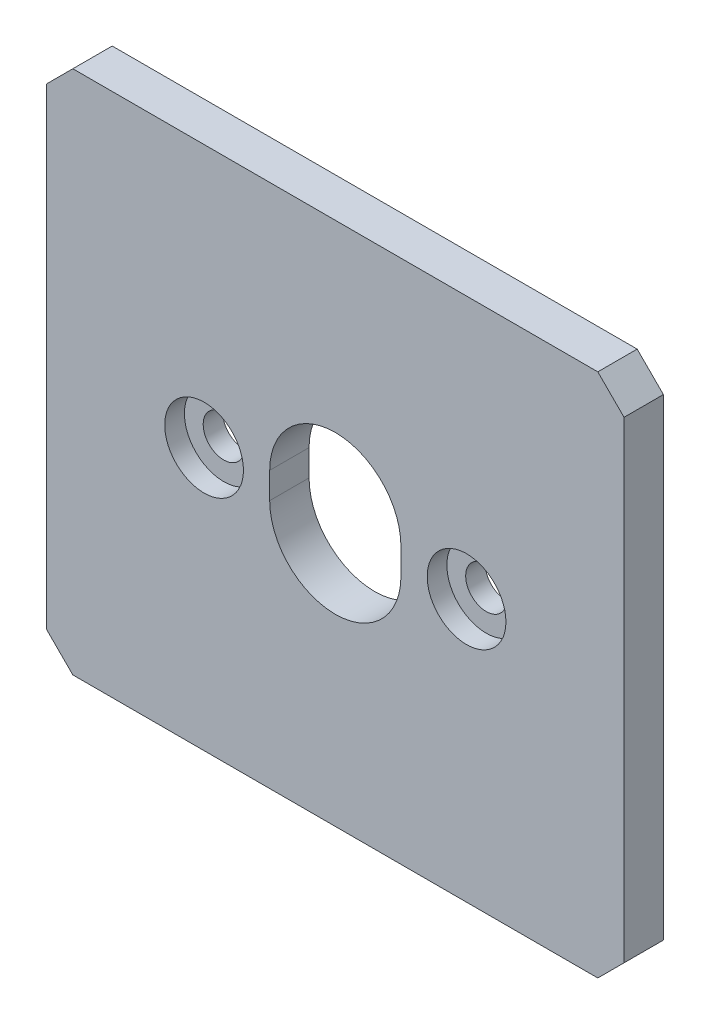
SolidWorks part; units mm, degrees
material "6063-T6"
ref_plane "Front Plane" through (0, 0, 0) normal (0, 0, 1) x (1, 0, 0)
ref_plane "Top Plane" through (0, 0, 0) normal (0, 1, 0) x (1, 0, 0)
ref_plane "Right Plane" through (0, 0, 0) normal (1, 0, 0) x (0, 0, -1)
sketch "Sketch1" plane through (0, 0, 0) normal (0, 0, 1) x (1, 0, 0)
  line L0 (0, 1.5875) -> (0, -1.5875) construction
  line L1 (-34.925, -31.75) -> (34.925, -31.75)
  line L2 (-34.925, -31.75) -> (-34.925, 31.75)
  line L3 (-34.925, 31.75) -> (34.925, 31.75)
  line L4 (34.925, -31.75) -> (34.925, 31.75)
  line L5 (-34.925, -31.75) -> (34.925, 31.75) construction
  line L6 (-34.925, 31.75) -> (34.925, -31.75) construction
  line L10 (-34.925, 0) -> (34.925, 0) construction
  line L11 (7.9375, 1.5875) -> (7.9375, -1.5875)
  line L12 (-7.9375, 1.5875) -> (-7.9375, -1.5875)
  circle A2 centre (-15.875, 0) radius 2.4892
  circle A3 centre (15.875, 0) radius 2.4892
  arc A4 (7.9375, 1.5875) -> (-7.9375, 1.5875) centre (0, 1.5875) ccw
  arc A5 (-7.9375, -1.5875) -> (7.9375, -1.5875) centre (0, -1.5875) ccw
  point P0 (0, 0)
  point P8 (0, 0)
  dimension "D5" = 4.9784
  dimension "D3" = 7.9375
  dimension "D1" = 63.5
  dimension "D2" = 69.85
  dimension "D6" = 19.05
  dimension "D7" = 19.05
  dimension "D8" = 31.75
  dimension "D4" = 1.5875
extrude "Boss-Extrude1" add sketch "Sketch1" along normal blind 4.7625
chamfer "Chamfer1" distance 3.175 angle 45 4 edges at (-34.925, -31.75, 2.3813) (34.925, -31.75, 2.3813) (-34.925, 31.75, 2.3813) (34.925, 31.75, 2.3813)
sketch "Sketch2" plane through (0, 0, 4.7625) normal (0, 0, 1) x (1, 0, 0)
  circle A0 centre (-15.875, 0) radius 4.7625
  circle A1 centre (15.875, 0) radius 4.7625
  dimension "D1" = 9.525
extrude "Cut-Extrude1" cut sketch "Sketch2" against normal blind 2.3813
equation "\"D8@Sketch1\"=\"D1@Sketch1\"/2"
